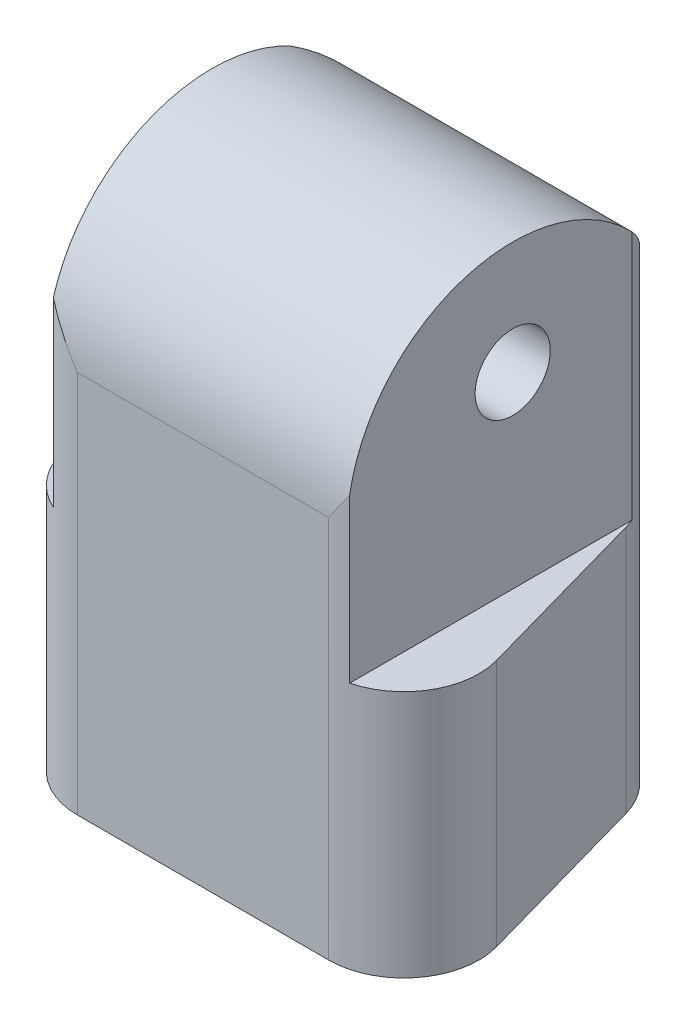
SolidWorks part; units mm, degrees
ref_plane "Front Plane" through (0, 0, 0) normal (0, 0, 1) x (1, 0, 0)
ref_plane "Top Plane" through (0, 0, 0) normal (0, 1, 0) x (1, 0, 0)
ref_plane "Right Plane" through (0, 0, 0) normal (1, 0, 0) x (0, 0, -1)
sketch "Sketch1" plane through (0, 0, 0) normal (0, 1, 0) x (1, 0, 0)
  line L0 (-8.3599, -8) -> (8.3599, -8)
  line L2 (-4.9849, 8) -> (4.9849, 8)
  line L3 (-6.9102, 6.5415) -> (-10.2852, -5.4585)
  line L4 (6.9102, 6.5415) -> (10.2852, -5.4585)
  line L8 (-8.3599, -11) -> (8.3599, -11)
  line L9 (9.7982, 7.3537) -> (13.1732, -4.6463)
  line L10 (-4.9849, 11) -> (4.9849, 11)
  line L11 (-9.7982, 7.3537) -> (-13.1732, -4.6463)
  arc A0 (8.3599, -8) -> (10.2852, -5.4585) centre (8.3599, -6) ccw
  arc A1 (-8.3599, -8) -> (-10.2852, -5.4585) centre (-8.3599, -6) cw
  arc A2 (-4.9849, 8) -> (-6.9102, 6.5415) centre (-4.9849, 6) ccw
  arc A3 (4.9849, 8) -> (6.9102, 6.5415) centre (4.9849, 6) cw
  arc A8 (8.3599, -11) -> (13.1732, -4.6463) centre (8.3599, -6) ccw
  arc A9 (4.9849, 11) -> (9.7982, 7.3537) centre (4.9849, 6) cw
  arc A10 (-4.9849, 11) -> (-9.7982, 7.3537) centre (-4.9849, 6) ccw
  arc A11 (-8.3599, -11) -> (-13.1732, -4.6463) centre (-8.3599, -6) cw
  point P11 (11, -8)
  point P14 (-11, -8)
  point P17 (-6.5, 8)
  point P20 (6.5, 8)
  dimension "D4" = 2
  dimension "D1" = 22
  dimension "D2" = 3
  dimension "D3" = 13
extrude "Boss-Extrude1" add sketch "Sketch1" along normal blind 15.5
sketch "Sketch2" plane through (0, 15.5, 0) normal (0, 1, 0) x (1, 0, 0)
  line L4 (-8.3599, -11) -> (8.3599, -11)
  line L5 (13.1732, -4.6463) -> (9.7982, 7.3537)
  line L6 (4.9849, 11) -> (-4.9849, 11)
  line L7 (-9.7982, 7.3537) -> (-13.1732, -4.6463)
  line L8 (-8.3599, -11) -> (8.3599, -11)
  line L9 (13.1732, -4.6463) -> (9.7982, 7.3537)
  line L10 (4.9849, 11) -> (-4.9849, 11)
  line L11 (-9.7982, 7.3537) -> (-13.1732, -4.6463)
  arc A4 (-13.1732, -4.6463) -> (-8.3599, -11) centre (-8.3599, -6) ccw
  arc A5 (8.3599, -11) -> (13.1732, -4.6463) centre (8.3599, -6) ccw
  arc A6 (9.7982, 7.3537) -> (4.9849, 11) centre (4.9849, 6) ccw
  arc A7 (-4.9849, 11) -> (-9.7982, 7.3537) centre (-4.9849, 6) ccw
  arc A8 (-13.1732, -4.6463) -> (-8.3599, -11) centre (-8.3599, -6) ccw
  arc A9 (8.3599, -11) -> (13.1732, -4.6463) centre (8.3599, -6) ccw
  arc A10 (9.7982, 7.3537) -> (4.9849, 11) centre (4.9849, 6) ccw
  arc A11 (-4.9849, 11) -> (-9.7982, 7.3537) centre (-4.9849, 6) ccw
  dimension "D1" = 0
extrude "Boss-Extrude2" add sketch "Sketch2" along normal blind 21
sketch "Sketch5" plane through (0, 0, 0) normal (0, 0, 1) x (1, 0, 0)
  line L0 (-8.3599, 36.5) -> (-13.3599, 36.5) construction
  line L1 (-15.4, 36.5) -> (-10.4, 36.5)
  line L2 (-15.4, 36.5) -> (-15.4, 16.5)
  line L3 (-15.4, 16.5) -> (-10.4, 16.5)
  line L4 (-10.4, 36.5) -> (-10.4, 16.5)
  line L5 (-15.4, 36.5) -> (-10.4, 16.5) construction
  line L6 (-15.4, 16.5) -> (-10.4, 36.5) construction
  line L7 (9.6, 36.5) -> (14.6, 36.5)
  line L8 (9.6, 36.5) -> (9.6, 16.5)
  line L9 (9.6, 16.5) -> (14.6, 16.5)
  line L10 (14.6, 36.5) -> (14.6, 16.5)
  line L11 (9.6, 36.5) -> (14.6, 16.5) construction
  line L12 (9.6, 16.5) -> (14.6, 36.5) construction
  line L13 (13.3599, 36.5) -> (8.3599, 36.5) construction
  line L14 (-8.3599, 36.5) -> (8.3599, 36.5) construction
  point P0 (-12.9, 26.5)
  point P7 (12.1, 26.5)
  point P16 (0, 36.5)
  dimension "D1" = 5
  dimension "D2" = 20
  dimension "D3" = 5
  dimension "D4" = 20
  dimension "D5" = 20
  dimension "D6" = 10.4
extrude "Cut-Extrude1" cut sketch "Sketch5" against normal through all both and the other way through all
sketch "Sketch6" plane through (9.6, 0, 0) normal (1, 0, 0) x (0, 0, -1)
  line L1 (7.9238, 36.5) -> (-10.8438, 36.5) construction
  line L2 (-11, 25.5) -> (-13.5119, 25.5)
  line L3 (-13.5119, 25.5) -> (-13.5119, 39.4755)
  line L4 (-13.5119, 39.4755) -> (12.5976, 39.0373)
  line L5 (12.5976, 39.0373) -> (12.5976, 25.5)
  line L6 (12.5976, 25.5) -> (11, 25.5)
  arc A0 (11, 25.5) -> (-11, 25.5) centre (0, 25.5) ccw
  dimension "D1" = 22
  dimension "D2" = 11
extrude "Cut-Extrude2" cut sketch "Sketch6" against normal through all
sketch "Sketch7" plane through (9.6, 0, 0) normal (1, 0, 0) x (0, 0, -1)
  line L0 (0, 36.5) -> (0, 29) construction
  circle A0 centre (0, 29) radius 2.5
  arc A1 (7.9238, 33.1298) -> (-10.8438, 27.3473) centre (0, 25.5) ccw construction
  dimension "D1" = 5
  dimension "D2" = 7.5
extrude "Cut-Extrude3" cut sketch "Sketch7" against normal through all
